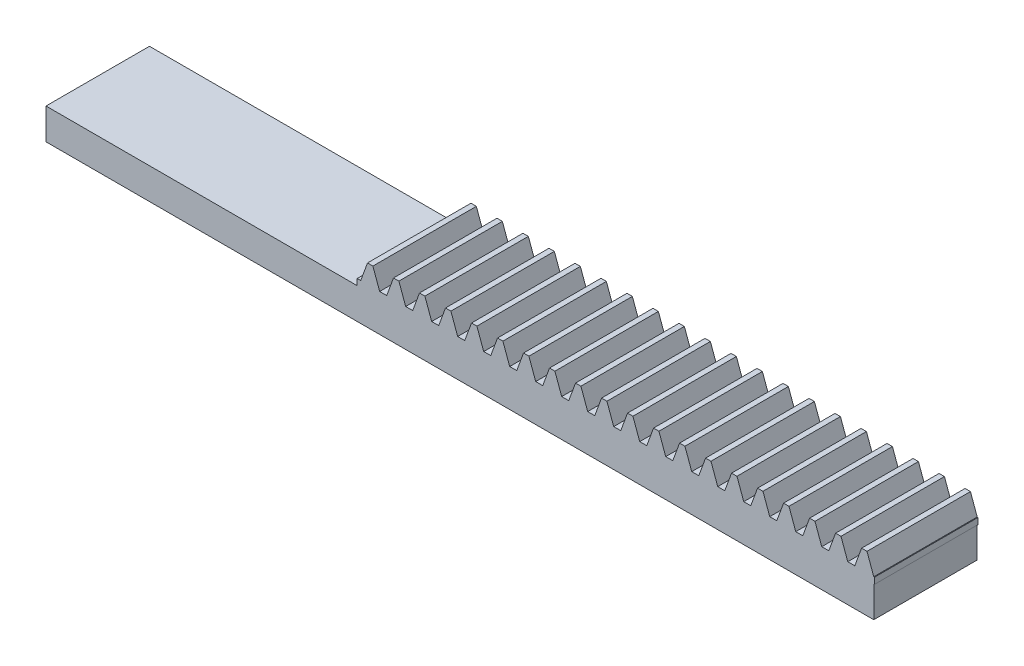
SolidWorks part; units mm, degrees
extrude "Blank" add sketch "BlankSke" against normal blind 100
sketch "BlankSke" plane through (0, 0, 0) normal (0, 0, 1) x (1, 0, 0)
  line L1 (0, 0) -> (500, 0)
  line L2 (0, 0) -> (0, 24)
  line L3 (0, 24) -> (500, 24)
  line L4 (500, 0) -> (500, 24)
  dimension "Length" = 500
  dimension "Blank_height" = 24
ref_plane "Plane1" through (0, 0, 0) normal (0, 0, 1) x (1, 0, 0)
ref_plane "Plane2" through (0, 0, 0) normal (0, 1, 0) x (1, 0, 0)
ref_plane "Plane3" through (0, 0, 0) normal (1, 0, 0) x (0, 0, -1)
sketch "HoldingSke" plane through (0, 0, 0) normal (0, 1, 0) x (1, 0, 0)
  line L0 (0, 0) -> (0.0174, 0.1238)
  line L1 (-15, 0) -> (100, 0) construction
  line L2 (0, 0) -> (-2.1039, 2.3779)
  line L3 (0, 0) -> (-11.863, 4.5341)
  line L4 (0, 0) -> (8.0624, 3.0949)
  line L5 (0, 0) -> (-23.7986, -8.8762)
  line L6 (0, 0) -> (-10.5278, -7.1032)
  line L9 (-71.009, 38.7566) -> (398.8373, 209.7667)
  line L10 (-76.2, 10.3779) -> (-60.2, 10.3779)
  line L11 (0, 0) -> (-100, 0)
  line L12 (-76.2, 101.6) -> (-75.945, 101.6)
  line L13 (24.9733, 27.94) -> (52.9518, 28.4284)
  line L14 (24.9733, 27.94) -> (24.9743, 27.94)
  line L15 (24.9733, 27.94) -> (100.4006, 29.5858)
  circle A0 centre (0, 0) radius 19.05
  circle A1 centre (0, 0) radius 8
  circle A2 centre (0, 0) radius 12.7
  dimension "MPH" = 16
  dimension "Diameter" = 38.1
  dimension "Num_teeth" = 21
  dimension "Pitch" = 0.125
  dimension "Show_teeth" = 998
  dimension "Thickness" = 12.7
  dimension "Ap" = 20
  dimension "Pitch_height" = 16
  dimension "Width" = 100
  dimension "Backlash" = 0.255
  dimension "Addendum_fac" = 1
  dimension "Dedendum_fac" = 1.25
  dimension "Clearance_fac" = 0.25
  dimension "Dedendum_add" = 0.001
  dimension "Length" = 500
  dimension "Module" = 8
sketch "TooCutSkeIll" plane through (0, 0, 0) normal (0, 0, 1) x (1, 0, 0)
  line L0 (-9.8833, 23.7894) -> (-3.8877, 7.3166)
  line L1 (-2.0074, 6) -> (2.0074, 6)
  line L2 (3.8877, 7.3166) -> (9.8833, 23.7894)
  line L3 (500, 24) -> (0, 24) construction
  line L4 (0, 0) -> (0, 64.897) construction
  line L5 (-13.208, 16) -> (12.954, 16) construction
  line L6 (0, 0) -> (500, 0) construction
  line L7 (7.0482, 16) -> (7.0482, 48.7463) construction
  line L8 (-7.0482, 16) -> (-7.0482, 48.7463) construction
  line L9 (10.184, 24) -> (10.184, 24.0254)
  line L10 (-10.184, 24) -> (-10.184, 24.0254)
  line L11 (-10.184, 24.0254) -> (10.184, 24.0254)
  arc A0 (2.0074, 6) -> (3.8877, 7.3166) centre (2.0074, 8.001) ccw
  arc A1 (-3.8877, 7.3166) -> (-2.0074, 6) centre (-2.0074, 8.001) ccw
  arc A2 (10.184, 24) -> (9.8833, 23.7894) centre (10.184, 23.68) ccw
  arc A3 (-9.8833, 23.7894) -> (-10.184, 24) centre (-10.184, 23.68) ccw
  dimension "Pitch_height" = 16
  dimension "Addendum_plus" = 8.0254
  dimension "Pressure_angle" = 20
  dimension "Gap_width" = 14.0964
  dimension "Dedendum" = 10
extrude "ToothCutIll" [suppressed] cut sketch "TooCutSkeIll" against normal through all
sketch "TooCutSkeSim" plane through (0, 0, 0) normal (0, 0, 1) x (1, 0, 0)
  line L0 (3.4085, 6) -> (-3.4085, 6)
  line L1 (9.9692, 24.0254) -> (3.4085, 6)
  line L2 (0, 17.4625) -> (0, 53.467) construction
  line L3 (9.9692, 24.0254) -> (-9.9692, 24.0254)
  line L6 (-9.9692, 24.0254) -> (-3.4085, 6)
  line L9 (-7.0482, 16) -> (7.0482, 16) construction
  line L10 (0, 0) -> (500, 0) construction
  line L11 (7.0482, 16) -> (7.0482, 53.467) construction
  line L12 (-7.0482, 16) -> (-7.0482, 53.467) construction
  dimension "Pitch_height" = 16
  dimension "Addendum_plus" = 8.0254
  dimension "Pressure_angle" = 20
  dimension "Gap_width" = 14.0964
  dimension "Dedendum" = 10
extrude "ToothCutSim" cut sketch "TooCutSkeSim" against normal through all
pattern_linear "TeethCuts" count 21 spacing 25.1327 along (1, 0, 0) of "ToothCutIll", "ToothCutSim"
sketch "Sketch1" plane through (0, 0, 0) normal (0, -1, 0) x (1, 0, 0)
  line L1 (499.2463, -100) -> (-300.7537, -100)
  line L2 (499.2463, -100) -> (499.2463, 0)
  line L3 (499.2463, 0) -> (-300.7537, 0)
  line L4 (-300.7537, -100) -> (-300.7537, 0)
  dimension "D1" = 800
extrude "Boss-Extrude1" add sketch "Sketch1" along normal blind 30
equation "' \"Module@HoldingSke\" = 6.35"
equation "' \"Num_teeth@HoldingSke\" = 12"
equation "' \"Ap@HoldingSke\" =  20"
equation "' \"Ap@HoldingSke\" = 20"
equation "' \"Width@HoldingSke\" = 0.25 * 25.4"
equation "' \"Show_teeth@HoldingSke\" = 500"
equation "' \"Backlash@HoldingSke\" = 0.009 * 25.4"
equation "' \"Addendum_fac@HoldingSke\" = 1.0"
equation "' \"Dedendum_fac@HoldingSke\" = 1.25"
equation "' \"Dedendum_add@HoldingSke\" = 0.00005 * 25.4"
equation "' \"Clearance_fac@HoldingSke\" = 0.25"
equation "' \"Pitch_height@HoldingSke\" = 1 * 25.4"
equation "' \"Length@HoldingSke\" = 4.71 * 25.4"
equation "\"Pitch@HoldingSke\" = 1 / \"Module@HoldingSke\""
equation "\"MPH@HoldingSke\" = \"Dedendum_fac@HoldingSke\" / \"Pitch@HoldingSke\" + 2 * \"Dedendum_add@HoldingSke\" + 0.002 * 25.4"
equation "\"MPH@HoldingSke\" = ((sgn( \"MPH@HoldingSke\" - \"Pitch_height@HoldingSke\")+1)*( \"MPH@HoldingSke\" - \"Pitch_height@HoldingSke\"))/2 + \"Pitch_height@HoldingSke\""
equation "\"Blank_height@BlankSke\" = \"Pitch_height@HoldingSke\" + \"Addendum_fac@HoldingSke\"  / \"Pitch@HoldingSke\" "
equation "\"Length@BlankSke\" =  \"Length@HoldingSke\""
equation "\"Face_width@Blank\" = \"Width@HoldingSke\""
equation "\"Pressure_angle@TooCutSkeIll\" = \"Ap@HoldingSke\""
equation "\"Addendum_plus@TooCutSkeIll\" =  \"Addendum_fac@HoldingSke\"  / \"Pitch@HoldingSke\" + 0.001 *25.4"
equation "\"Dedendum@TooCutSkeIll\" = \"Dedendum_fac@HoldingSke\"  / \"Pitch@HoldingSke\""
equation "\"Pitch_height@TooCutSkeIll\" =  \"MPH@HoldingSke\""
equation "\"Gap_width@TooCutSkeIll\" = 3.14159265 / 2 / \"Pitch@HoldingSke\" + 6 * \"Backlash@HoldingSke\""
equation "\"Pressure_angle@TooCutSkeSim\" = \"Ap@HoldingSke\""
equation "\"Addendum_plus@TooCutSkeSim\" =  \"Addendum_fac@HoldingSke\"  / \"Pitch@HoldingSke\" + 0.001 * 25.4"
equation "\"Dedendum@TooCutSkeSim\" = \"Dedendum_fac@HoldingSke\"  / \"Pitch@HoldingSke\""
equation "\"Pitch_height@TooCutSkeSim\" =  \"MPH@HoldingSke\""
equation "\"Gap_width@TooCutSkeSim\" = 3.14159265 / 2 / \"Pitch@HoldingSke\" + 6 * \"Backlash@HoldingSke\""
equation "\"Root_fillet@TooCutSkeIll\" = \"Clearance_fac@HoldingSke\" / \"Pitch@HoldingSke\" + \"Dedendum_add@HoldingSke\""
equation "\"Break_rad@TooCutSkeIll\" = 0.02 / \"Pitch@HoldingSke\" * 2"
equation "\"Linear_pitch@TeethCuts\" = 3.14159265 / \"Pitch@HoldingSke\""
equation "\"Num_teeth@HoldingSke\" = int( ( \"Length@HoldingSke\" + 0 ) / (3.14159265 / \"Pitch@HoldingSke\")) + 0.9999  + 1"
equation " \"Num_teeth@TeethCuts\" = int( \"Show_teeth@HoldingSke\" ) + 1"
equation " \"Num_teeth@TeethCuts\" = ((sgn( \"Num_teeth@TeethCuts\" - \"Num_teeth@HoldingSke\" )-1)*( \"Num_teeth@TeethCuts\" - \"Num_teeth@HoldingSke\" ))/-2+ \"Num_teeth@HoldingSke\""
equation " \"Num_teeth@TeethCuts\" = ((sgn( \"Num_teeth@TeethCuts\" - 2.0)+1)*( \"Num_teeth@TeethCuts\" - 2.0))/2 +2.0"
